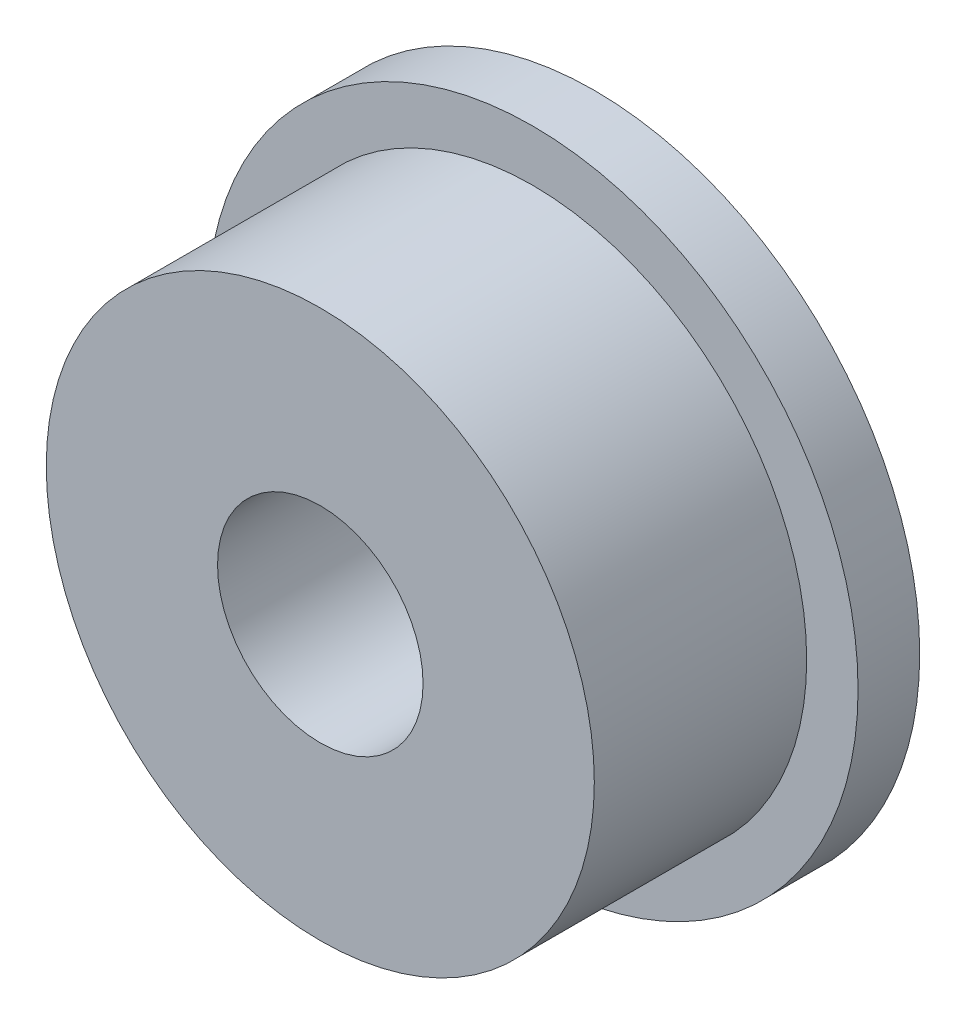
SolidWorks part; units mm, degrees
material "AISI 4340 Steel, normalized"
ref_plane "Front Plane" through (0, 0, 0) normal (0, 0, 1) x (1, 0, 0)
ref_plane "Top Plane" through (0, 0, 0) normal (0, 1, 0) x (1, 0, 0)
ref_plane "Right Plane" through (0, 0, 0) normal (1, 0, 0) x (0, 0, -1)
sketch "Sketch1" plane through (0, 0, 0) normal (0, 0, 1) x (1, 0, 0)
  circle A0 centre (0, 0) radius 4
  circle A1 centre (0, 0) radius 1.5
extrude "F693ZZ_External_Envelope_3x8x4" add sketch "Sketch1" along normal blind 4 from offset 2.5
sketch "Sketch2" plane through (0, 0, 0) normal (0, 0, 1) x (1, 0, 0)
  circle A0 centre (0, 0) radius 4.75
  circle A1 centre (0, 0) radius 1.5
extrude "Flange_9p5x0p9" add sketch "Sketch2" along normal blind 0.9 from offset 2.5
